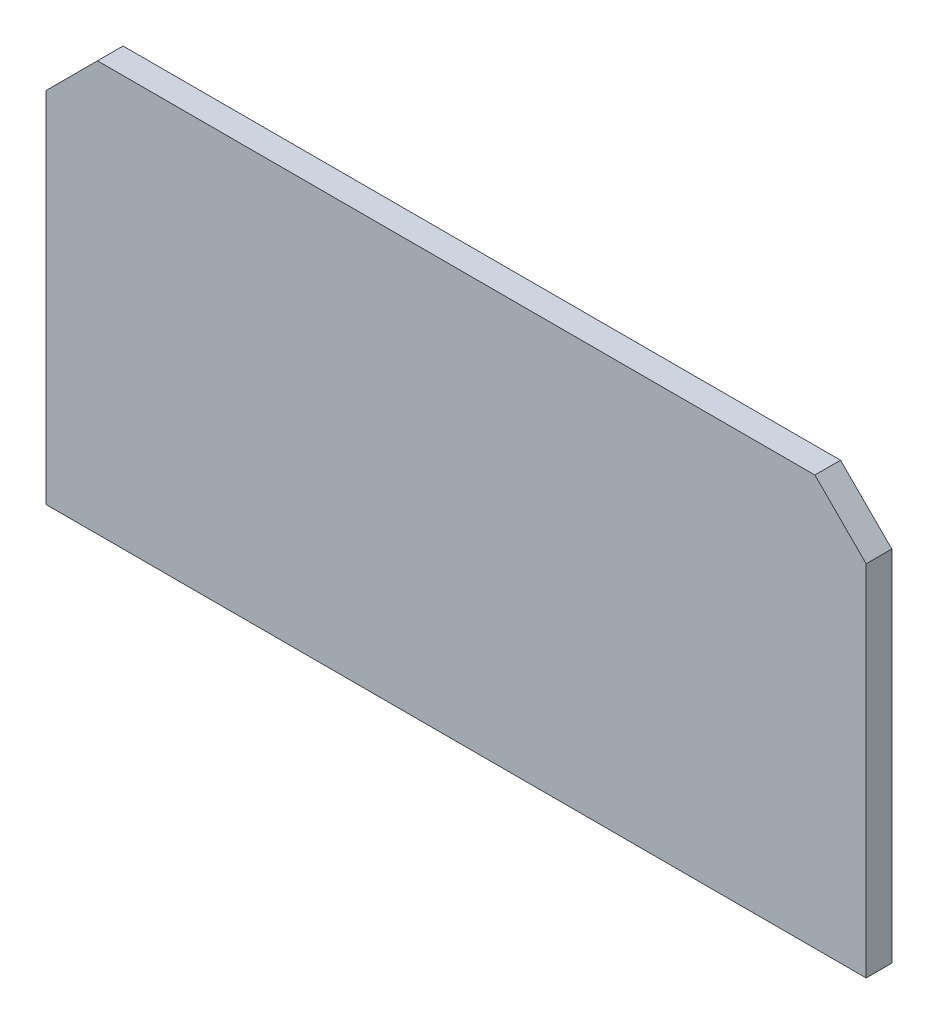
SolidWorks part; units mm, degrees
ref_plane "Front Plane" through (0, 0, 0) normal (0, 0, 1) x (1, 0, 0)
ref_plane "Top Plane" through (0, 0, 0) normal (0, 1, 0) x (1, 0, 0)
ref_plane "Right Plane" through (0, 0, 0) normal (1, 0, 0) x (0, 0, -1)
sketch "Sketch15" plane through (0, 0, 0) normal (0, 0, 1) x (1, 0, 0)
  line L0 (0, 44.45) -> (6.35, 50.8)
  line L1 (0, 0) -> (101.6, 0)
  line L2 (0, 0) -> (0, 44.45)
  line L3 (6.35, 50.8) -> (95.25, 50.8)
  line L4 (101.6, 0) -> (101.6, 44.45)
  line L5 (95.25, 50.8) -> (101.6, 44.45)
  point P1 (101.6, 50.8)
  point P2 (0, 50.8)
  point P9 (50.8, 14.0797)
extrude "Extrude10" add sketch "Sketch15" against normal blind 3.175
sketch "Sketch16" plane through (0, 0, 0) normal (0, 0, 1) x (1, 0, 0)
  line L0 (69.3015, 20.5856) -> (84.7148, 20.5856)
  line L4 (16.8852, 20.5856) -> (32.2985, 20.5856)
  arc A0 (32.2985, 20.5856) -> (69.3015, 20.5856) centre (50.8, 17.635) cw
  dimension "D3" = 10
  dimension "D4" = 10
  dimension "D5" = 6.35
  dimension "D6" = 6.35
  dimension "D7" = 6.35
  dimension "D8" = 6.35
